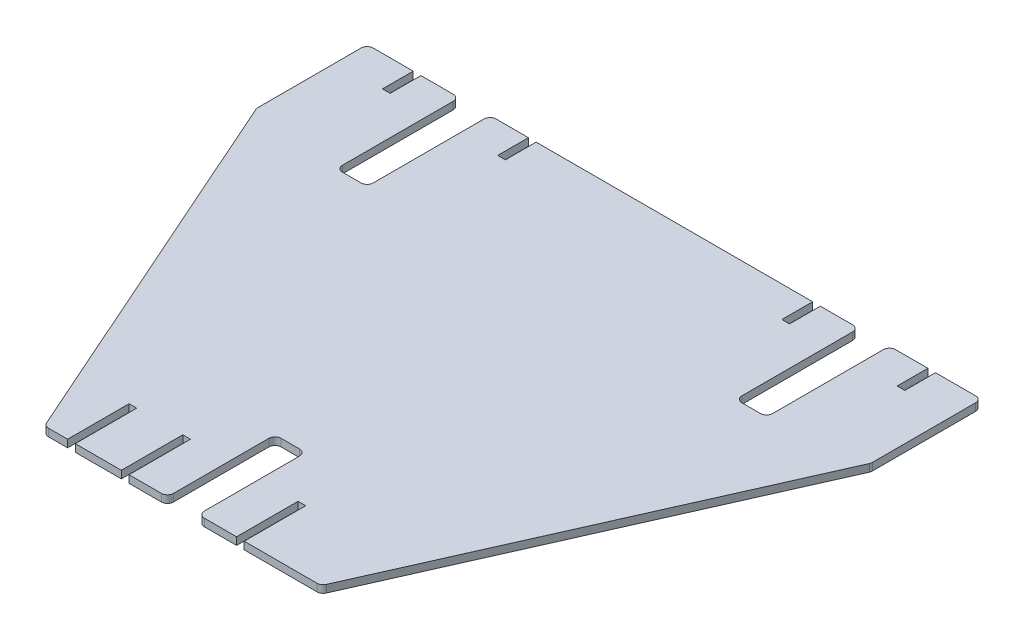
SolidWorks part; units mm, degrees
material "Corrugated Paper"
ref_plane "Front Plane" through (0, 0, 0) normal (0, 0, 1) x (1, 0, 0)
ref_plane "Top Plane" through (0, 0, 0) normal (0, 1, 0) x (1, 0, 0)
ref_plane "Right Plane" through (0, 0, 0) normal (1, 0, 0) x (0, 0, -1)
sketch "Sketch1" plane through (0, 0, 0) normal (0, 1, 0) x (1, 0, 0)
  line L0 (0, 0) -> (0, -142.875) construction
  line L1 (6.35, -57.15) -> (-6.35, -57.15)
  line L2 (-6.35, -57.15) -> (-6.35, -101.6)
  line L3 (-6.35, -101.6) -> (-22.225, -101.6)
  line L4 (-57.15, -101.6) -> (-127, 55.88)
  line L5 (-127, 55.88) -> (-127, 101.6)
  line L6 (-127, 101.6) -> (-107.95, 101.6)
  line L7 (-88.9, 101.6) -> (-88.9, 50.8)
  line L9 (-88.9, 50.8) -> (-76.2, 50.8)
  line L10 (-76.2, 50.8) -> (-76.2, 101.6)
  line L11 (-76.2, 101.6) -> (-60.325, 101.6)
  line L13 (76.2, 50.8) -> (76.2, 101.6)
  line L14 (88.9, 50.8) -> (76.2, 50.8)
  line L15 (88.9, 101.6) -> (88.9, 50.8)
  line L16 (127, 101.6) -> (107.95, 101.6)
  line L17 (127, 55.88) -> (127, 101.6)
  line L18 (57.15, -101.6) -> (127, 55.88)
  line L19 (6.35, -101.6) -> (22.225, -101.6)
  line L20 (6.35, -57.15) -> (6.35, -101.6)
  line L21 (-127, 101.6) -> (127, -101.6) construction
  line L22 (-25.4, -101.6) -> (-44.45, -101.6)
  line L24 (-25.4, -101.6) -> (-25.4, -76.2)
  line L25 (-25.4, -76.2) -> (-22.225, -76.2)
  line L26 (-22.225, -101.6) -> (-22.225, -76.2)
  line L27 (25.4, -101.6) -> (25.4, -76.2)
  line L28 (25.4, -76.2) -> (22.225, -76.2)
  line L29 (22.225, -101.6) -> (22.225, -76.2)
  line L30 (25.4, -101.6) -> (57.15, -101.6)
  line L31 (-82.55, 50.8) -> (-82.55, 101.6) construction
  line L32 (-104.775, 101.6) -> (-88.9, 101.6)
  line L34 (-107.95, 101.6) -> (-107.95, 88.9)
  line L35 (-107.95, 88.9) -> (-104.775, 88.9)
  line L36 (-104.775, 101.6) -> (-104.775, 88.9)
  line L37 (-57.15, 101.6) -> (-57.15, 88.9)
  line L38 (-57.15, 88.9) -> (-60.325, 88.9)
  line L39 (-60.325, 101.6) -> (-60.325, 88.9)
  line L40 (-57.15, 101.6) -> (57.15, 101.6)
  line L41 (107.95, 101.6) -> (107.95, 88.9)
  line L42 (107.95, 88.9) -> (104.775, 88.9)
  line L43 (104.775, 101.6) -> (104.775, 88.9)
  line L44 (57.15, 101.6) -> (57.15, 88.9)
  line L45 (60.325, 101.6) -> (60.325, 88.9)
  line L46 (57.15, 88.9) -> (60.325, 88.9)
  line L47 (60.325, 101.6) -> (76.2, 101.6)
  line L48 (104.775, 101.6) -> (88.9, 101.6)
  line L49 (-47.625, -101.6) -> (-47.625, -76.2)
  line L50 (-47.625, -76.2) -> (-44.45, -76.2)
  line L51 (-44.45, -76.2) -> (-44.45, -101.6)
  line L52 (-47.625, -101.6) -> (-57.15, -101.6)
  point P26 (0, -57.15)
  dimension "D2" = 12.7
  dimension "D3" = 254
  dimension "D5" = 44.45
  dimension "D6" = 50.8
  dimension "D7" = 203.2
  dimension "D8" = 45.72
  dimension "D10" = 3.175
  dimension "D11" = 25.4
  dimension "D12" = 3.175
  dimension "D4" = 114.3
  dimension "D13" = 50.8
  dimension "D9" = 50.8
  dimension "D14" = 38.1
  dimension "D15" = 12.7
  dimension "D16" = 19.05
extrude "Boss-Extrude1" add sketch "Sketch1" along normal blind 3.0988 contours L13 L47 L45 L46 L44 L40 L37 L38 L39 L11 L10 L9 L7 L32 L36 L35 L34 L6 L5 L4 L52 L49 L50 L51 L22 L24 L25 L26 L3 L2 L1 L20 L19 L29 L28 L27 L30 L18 L17 L16 L41 L42 L43 L48 L15 L14
fillet "Fillet1" radius 2.54 18 edges at (88.9, 1.5494, -50.8) (88.9, 1.5494, -101.6) (6.35, 1.5494, 101.6) (6.35, 1.5494, 57.15) (-6.35, 1.5494, 57.15) (-6.35, 1.5494, 101.6) (-127, 1.5494, -55.88) (-127, 1.5494, -101.6) (-88.9, 1.5494, -101.6) (-88.9, 1.5494, -50.8) (-76.2, 1.5494, -50.8) (-76.2, 1.5494, -101.6) (76.2, 1.5494, -101.6) (76.2, 1.5494, -50.8) (127, 1.5494, -101.6) (127, 1.5494, -55.88) (57.15, 1.5494, 101.6) (-57.15, 1.5494, 101.6)
sketch "Sketch4" plane through (0, 3.0988, 0) normal (0, 1, 0) x (1, 0, 0)
  line L0 (0, -164.31) -> (0, 101.6) construction
  line L1 (-63.105, 101.6) -> (63.105, 101.6) construction
  line L2 (-63.105, 101.6) -> (-63.105, -164.31) construction
  line L3 (-63.105, -164.31) -> (63.105, -164.31) construction
  line L4 (63.105, 101.6) -> (63.105, -164.31) construction
  line L5 (57.8198, -100.0899) -> (126.7819, 55.3882) construction
  line L6 (65.3301, -83.1577) -> (50.405, -83.1577)
  line L7 (65.3301, -83.1577) -> (65.3301, -88.1742)
  line L8 (65.3301, -88.1742) -> (50.405, -88.1742)
  line L9 (50.405, -83.1577) -> (50.405, -88.1742)
  line L10 (-50.405, -83.1577) -> (-50.405, -88.1742)
  line L11 (-65.3301, -88.1742) -> (-50.405, -88.1742)
  line L12 (-65.3301, -83.1577) -> (-65.3301, -88.1742)
  line L13 (-65.3301, -83.1577) -> (-50.405, -83.1577)
  line L14 (-57.15, 101.6) -> (57.15, 101.6) construction
  line L15 (-1.5875, 101.6) -> (1.5875, 101.6)
  line L16 (-1.5875, 101.6) -> (-1.5875, 88.9)
  line L17 (-1.5875, 88.9) -> (1.5875, 88.9)
  line L18 (1.5875, 101.6) -> (1.5875, 88.9)
  point P8 (63.105, -88.1742)
  point P11 (0, 101.6)
  dimension "D1" = 265.91
  dimension "D2" = 126.21
  dimension "D5" = 3.175
  dimension "D6" = 12.7
  dimension "D4" = 12.7
  dimension "D3" = 5.0165
extrude "Cut-Extrude3" [suppressed] cut sketch "Sketch4" against normal through all
equation "\"D1@Boss-Extrude1\" = \"thick\""
equation "\"D10@Sketch1\"=\"thick\"+\"clear\""
equation "\"D12@Sketch1\"=\"thick\"+\"clear\""
equation "\"rodThick\"= 0.085in"
equation "\"thick\"= 0.122in"
equation "\"clear\"= 0.003in"
equation "\"D5@Sketch4\"=\"thick\"+\"clear\""
